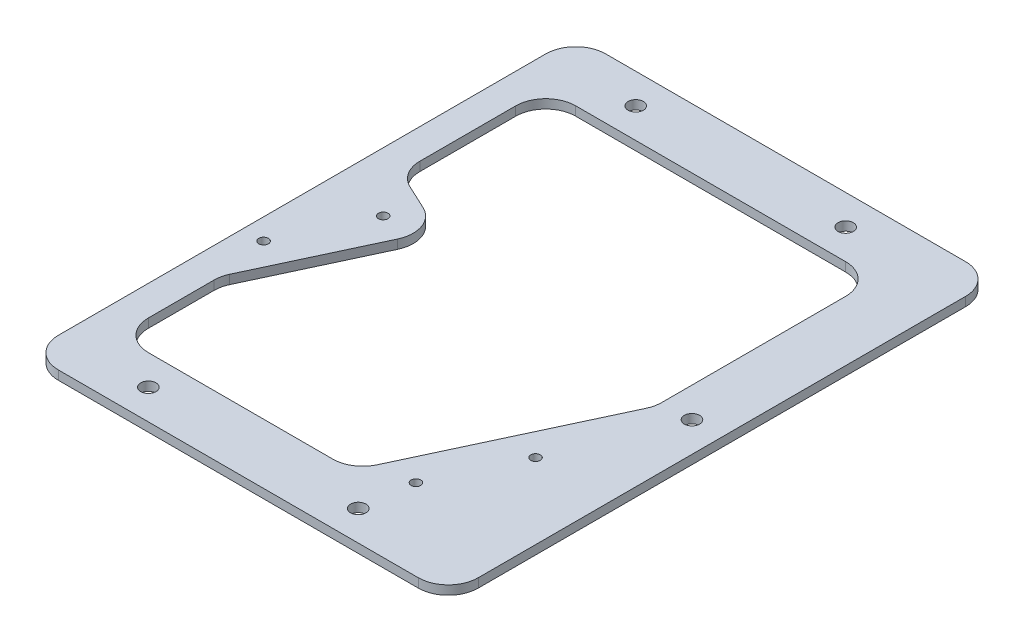
SolidWorks part; units mm, degrees
ref_plane "正面" through (0, 0, 0) normal (0, 0, 1) x (1, 0, 0)
ref_plane "平面" through (0, 0, 0) normal (0, 1, 0) x (1, 0, 0)
ref_plane "右側面" through (0, 0, 0) normal (1, 0, 0) x (0, 0, -1)
sketch "ｽｹｯﾁ1" plane through (0, 0, 0) normal (0, 1, 0) x (1, 0, 0)
  line L0 (-70, 81.25) -> (60, 81.25) construction
  line L1 (-70, 91.25) -> (70, 91.25)
  line L2 (-70, 91.25) -> (-70, -91.25)
  line L3 (-70, -91.25) -> (70, -91.25)
  line L4 (70, 91.25) -> (70, -91.25)
  line L5 (-70, 91.25) -> (70, -91.25) construction
  line L6 (-70, -91.25) -> (70, 91.25) construction
  line L7 (60, 81.25) -> (60, -81.25) construction
  line L8 (60, -81.25) -> (-70, -81.25) construction
  line L9 (-40, 81.25) -> (-40, -81.25) construction
  line L10 (30, 81.25) -> (30, -81.25) construction
  circle A0 centre (-40, 81.25) radius 2.55
  circle A1 centre (30, 81.25) radius 2.55
  circle A2 centre (60, 0) radius 2.55
  circle A3 centre (-40, -81.25) radius 2.55
  circle A4 centre (30, -81.25) radius 2.55
  point P0 (0, 0)
  dimension "D6" = 30
  dimension "D8" = 5.1
  dimension "D1" = 182.5
  dimension "D2" = 140
  dimension "D3" = 10
  dimension "D4" = 10
  dimension "D5" = 10
  dimension "D7" = 40
extrude "ﾎﾞｽ - 押し出し1" add sketch "ｽｹｯﾁ1" along normal blind 3
fillet "ﾌｨﾚｯﾄ1" radius 10 4 edges at (-70, 1.5, -91.25) (70, 1.5, -91.25) (-70, 1.5, 91.25) (70, 1.5, 91.25)
sketch "ｽｹｯﾁ2" plane through (0, 3, 0) normal (0, 1, 0) x (1, 0, 0)
  line L0 (-70, 0) -> (70, -65.2831) construction
  line L1 (-70, 81.25) -> (-70, -81.25) construction
  line L2 (-70, 0) -> (0, 0) construction
  line L3 (70, -81.25) -> (70, 81.25) construction
  line L4 (0, -32.6415) -> (57.7716, 91.25) construction
  line L5 (60, 91.25) -> (-60, 91.25) construction
  line L6 (-50.305, 7.3667) -> (-62.9835, -19.8225) construction
  line L7 (-62.9835, -19.8225) -> (32.1788, -64.1974) construction
  line L8 (32.1788, -64.1974) -> (44.8574, -37.0082) construction
  line L9 (44.8574, -37.0082) -> (-50.305, 7.3667) construction
  line L10 (-62.9835, -19.8225) -> (44.8574, -37.0082) construction
  line L11 (-50.305, 7.3667) -> (32.1788, -64.1974) construction
  circle A0 centre (-50.305, 7.3667) radius 1.6
  circle A1 centre (-62.9835, -19.8225) radius 1.6
  circle A2 centre (44.8574, -37.0082) radius 1.6
  circle A3 centre (32.1788, -64.1974) radius 1.6
  point P16 (-9.0631, -28.4154)
  point P21 (0, 0)
  point P22 (0, -32.6415)
  point P23 (0, -32.6415)
  point P24 (0, 0)
  point P25 (-4.5315, -30.5284)
  dimension "D4" = 3.2
  dimension "D1" = 25
  dimension "D2" = 105
  dimension "D3" = 30
  dimension "D5" = 10
extrude "ｶｯﾄ - 押し出し1" cut sketch "ｽｹｯﾁ2" against normal through all
sketch "ｽｹｯﾁ3" plane through (0, 3, 0) normal (0, 1, 0) x (1, 0, 0)
  line L0 (-60, 71.25) -> (50, 71.25)
  line L1 (50, 71.25) -> (50, -2.3177)
  line L2 (50, -2.3177) -> (17.8564, -71.25)
  line L3 (17.8564, -71.25) -> (-60, -71.25)
  line L4 (-60, -71.25) -> (-60, -37.0864)
  line L5 (-60, -37.0864) -> (-37.0157, 12.2036)
  line L6 (-37.0157, 12.2036) -> (-60, 22.9214)
  line L7 (-60, 22.9214) -> (-60, 71.25)
  line L8 (60, 91.25) -> (-60, 91.25) construction
  line L9 (70, -81.25) -> (70, 81.25) construction
  line L10 (-70, 81.25) -> (-70, -81.25) construction
  line L11 (-60, -91.25) -> (60, -91.25) construction
  line L12 (-50.305, 7.3667) -> (-62.9835, -19.8225) construction
  line L13 (44.8574, -37.0082) -> (32.1788, -64.1974) construction
  dimension "D1" = 20
  dimension "D2" = 20
  dimension "D3" = 10
  dimension "D4" = 10
  dimension "D5" = 20
  dimension "D6" = 10
  dimension "D7" = 10
  dimension "D8" = 10
extrude "ｶｯﾄ - 押し出し2" cut sketch "ｽｹｯﾁ3" against normal through all
fillet "ﾌｨﾚｯﾄ2" radius 10 8 edges at (50, 1.5, 2.3177) (17.8564, 1.5, 71.25) (-60, 1.5, 71.25) (-60, 1.5, 37.0864) (-37.0157, 1.5, -12.2036) (-60, 1.5, -22.9214) (50, 1.5, -71.25) (-60, 1.5, -71.25)
